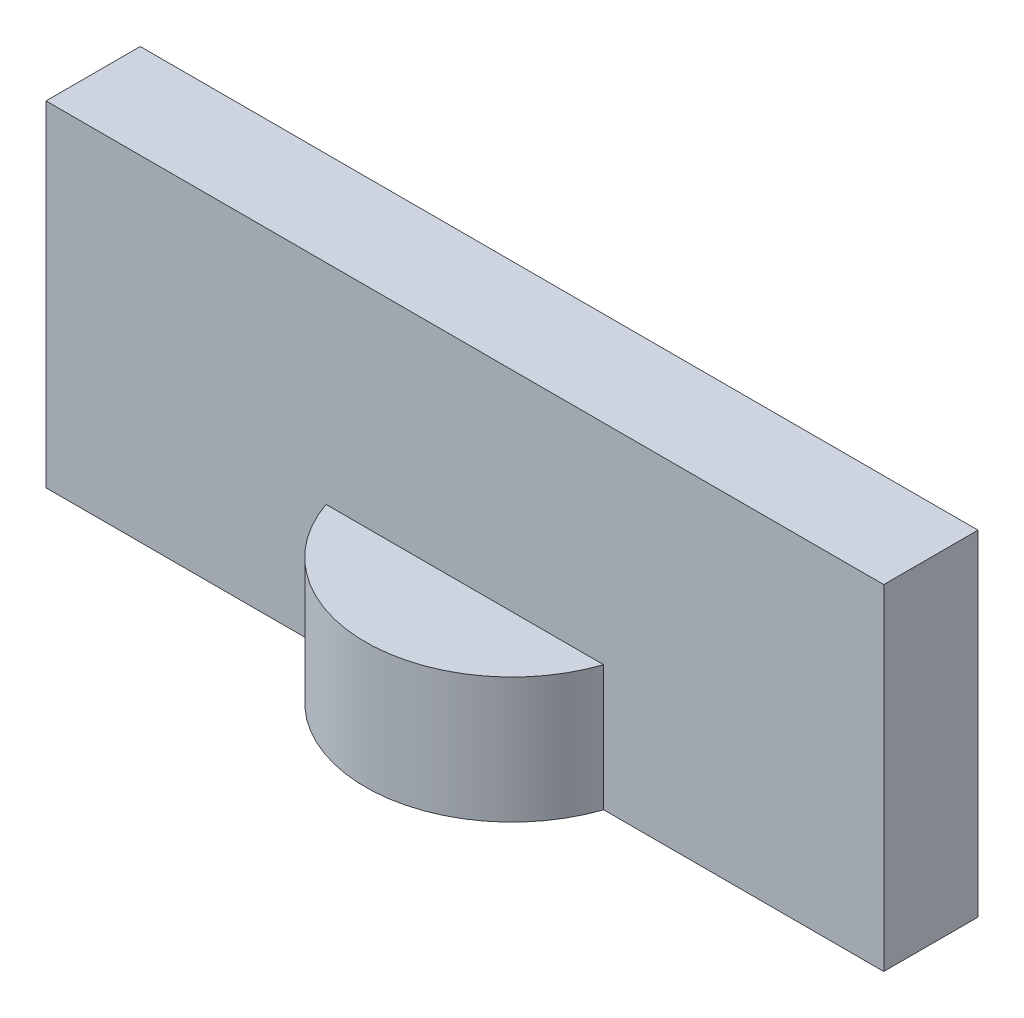
SolidWorks part; units mm, degrees
ref_plane "Front Plane" through (0, 0, 0) normal (0, 0, 1) x (1, 0, 0)
ref_plane "Top Plane" through (0, 0, 0) normal (0, 1, 0) x (1, 0, 0)
ref_plane "Right Plane" through (0, 0, 0) normal (1, 0, 0) x (0, 0, -1)
sketch "Sketch1" plane through (0, 0, 0) normal (0, 1, 0) x (1, 0, 0)
  circle A0 centre (0, 0) radius 4.445
  dimension "D1" = 8.89
extrude "Boss-Extrude1" add sketch "Sketch1" along normal blind 3.81
sketch "Sketch2" plane through (0, 0, 0) normal (0, 1, 0) x (1, 0, 0)
  line L1 (12.7, -1.4287) -> (-12.7, -1.4288)
  line L2 (12.7, -1.4287) -> (12.7, 1.4288)
  line L3 (12.7, 1.4288) -> (-12.7, 1.4287)
  line L4 (-12.7, -1.4288) -> (-12.7, 1.4287)
  line L5 (12.7, -1.4287) -> (-12.7, 1.4287) construction
  line L6 (12.7, 1.4288) -> (-12.7, -1.4288) construction
  point P0 (0, 0)
  dimension "D1" = 25.4
  dimension "D2" = 2.8575
extrude "Boss-Extrude2" add sketch "Sketch2" along normal blind 10.16
